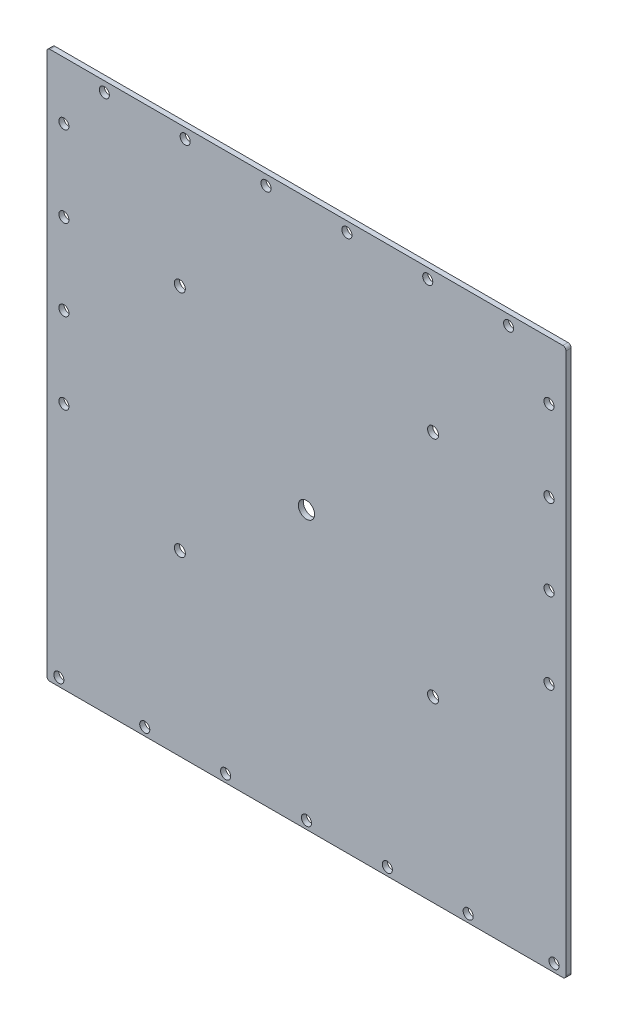
SolidWorks part; units mm, degrees
material "6061 Alloy"
ref_plane "Front Plane" through (0, 0, 0) normal (0, 0, 1) x (1, 0, 0)
ref_plane "Top Plane" through (0, 0, 0) normal (0, 1, 0) x (1, 0, 0)
ref_plane "Right Plane" through (0, 0, 0) normal (1, 0, 0) x (0, 0, -1)
sketch "Sketch2" plane through (0, 0, 0) normal (0, 0, 1) x (1, 0, 0)
  line L0 (0, -176.7623) -> (165.1, -176.7623)
  line L1 (0, 0) -> (165.1, 0)
  line L5 (82.55, 0) -> (82.55, -176.7623) construction
  line L6 (165.1, 0) -> (165.1, -176.7623)
  line L7 (0, 0) -> (0, -176.7623)
  line L8 (0, 0) -> (0, -176.7623)
  line L9 (0, -171.98) -> (165.1, -171.98)
  line L10 (1, 0) -> (1, -171.98)
  line L11 (164.1, -171.98) -> (164.1, 0)
  circle A31 centre (31.75, -169.48) radius 1.5875
  circle A32 centre (57.15, -169.48) radius 1.5875
  circle A33 centre (82.55, -169.48) radius 1.5875
  circle A34 centre (107.95, -169.48) radius 1.5875
  circle A35 centre (133.35, -169.48) radius 1.5875
  circle A63 centre (6.35, -18.05) radius 1.5875
  circle A65 centre (160.3375, -169.48) radius 1.5875
  circle A66 centre (4.7625, -169.48) radius 1.5875
  circle A67 centre (82.55, -85) radius 2.5527
  circle A69 centre (19.05, -3.175) radius 1.5875
  circle A70 centre (44.45, -3.175) radius 1.5875
  circle A71 centre (69.85, -3.175) radius 1.5875
  circle A72 centre (95.25, -3.175) radius 1.5875
  circle A73 centre (120.65, -3.175) radius 1.5875
  circle A74 centre (146.05, -3.175) radius 1.5875
  circle A76 centre (6.35, -43.45) radius 1.5875
  circle A77 centre (6.35, -68.85) radius 1.5875
  circle A78 centre (6.35, -94.25) radius 1.5875
  circle A81 centre (158.75, -68.85) radius 1.5875
  circle A82 centre (158.75, -94.25) radius 1.5875
  circle A83 centre (158.75, -43.45) radius 1.5875
  circle A84 centre (158.75, -18.05) radius 1.5875
  dimension "D9" = 3.175
  dimension "D4" = 3.175
  dimension "D21" = 5.1054
  dimension "D1" = 165.1
  dimension "D23" = 25.4
  dimension "D5" = 176.7623
  dimension "D8" = 31.75
  dimension "D11" = 7.2823
  dimension "D10" = 19.05
  dimension "D12" = 3.175
  dimension "D14" = 25.4
  dimension "D3" = 18.05
  dimension "D6" = 6.35
  dimension "D15" = 25.4
  dimension "D16" = 2.5
  dimension "D17" = 4.7625
  dimension "D18" = 1
  dimension "D19" = 1
  dimension "D20" = 85
  dimension "D22" = 5
  dimension "D13" = 3
  dimension "D7" = 4
extrude "Boss-Extrude2" add sketch "Sketch2" along normal blind 1.6
fillet "Fillet1" radius 1 4 edges at (1, -171.98, 0.8) (1, 0, 0.8) (164.1, 0, 0.8) (164.1, -171.98, 0.8)
sketch "Sketch5" plane through (0, 0, 1.6) normal (0, 0, 1) x (1, 0, 0)
  line L0 (122.325, -43.995) -> (122.325, -115.985) construction
  line L1 (42.775, -43.995) -> (122.325, -43.995) construction
  line L7 (42.775, -43.995) -> (42.775, -115.985) construction
  line L9 (42.775, -115.985) -> (122.325, -115.985) construction
  line L10 (2, 0) -> (2, -171.98) construction
  line L11 (1, -1) -> (164.1, -1) construction
  circle A0 centre (82.55, -85) radius 2.5527 construction
  circle A1 centre (42.775, -43.995) radius 1.725
  circle A2 centre (122.325, -43.995) radius 1.725
  circle A3 centre (122.325, -115.985) radius 1.725
  circle A4 centre (42.775, -115.985) radius 1.725
  point P4 (82.55, -85)
  point P15 (82.55, -43.995)
  dimension "D3" = 3.45
  dimension "D1" = 163.1
  dimension "D2" = 171.98
  dimension "D4" = 42.995
  dimension "D5" = 40.775
  dimension "D6" = 55.995
extrude "Cut-Extrude1" cut sketch "Sketch5" against normal through all both and the other way through all
equation "\"D19@Sketch2\"=\"D18@Sketch2\""
equation "\"D9@Sketch2\"=\"D4@Sketch2\""
equation "\"D4@Sketch5\"=\"D2@Sketch5\"/4"
equation "\"D5@Sketch5\"=\"D1@Sketch5\"/4"
equation "\"D6@Sketch5\"=\"D2@Sketch5\"/4 +13"
